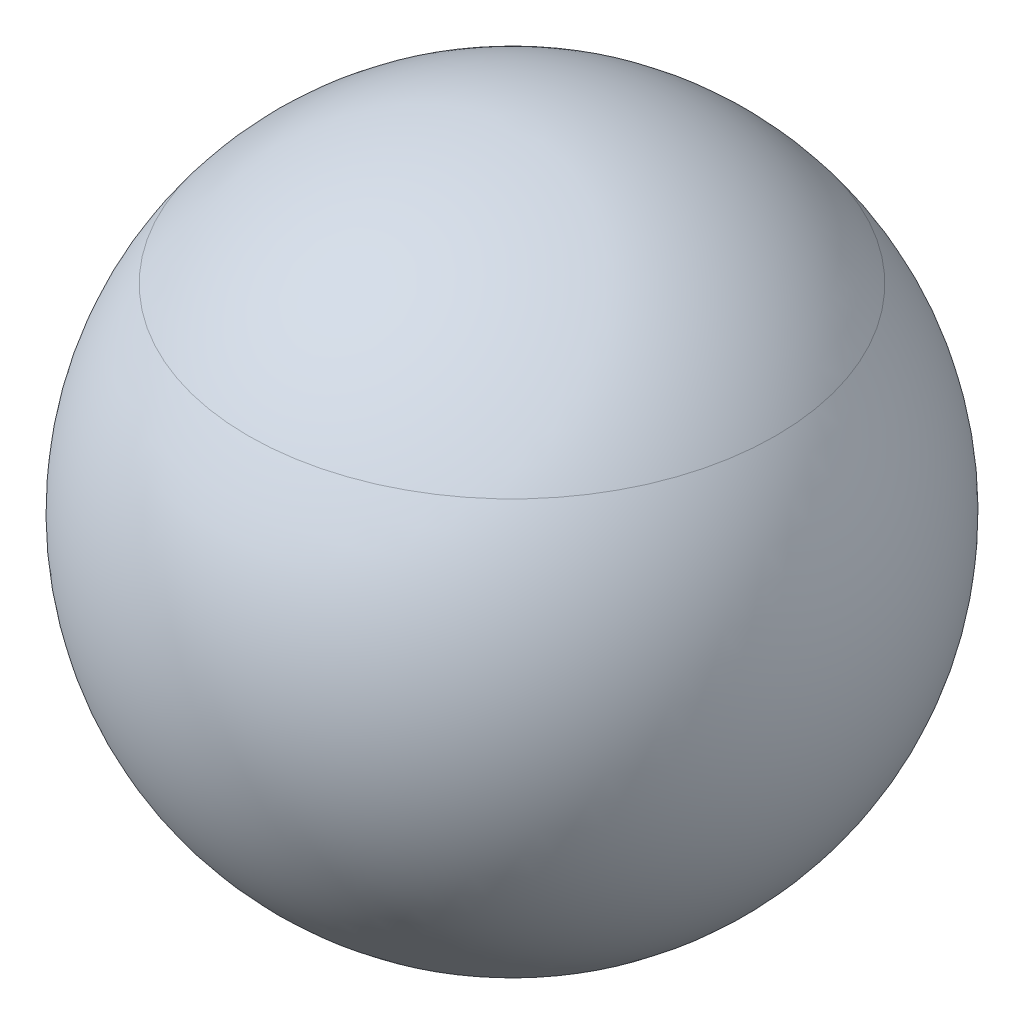
SolidWorks part; units mm, degrees
ref_plane "Front Plane" through (0, 0, 0) normal (0, 0, 1) x (1, 0, 0)
ref_plane "Top Plane" through (0, 0, 0) normal (0, 1, 0) x (1, 0, 0)
ref_plane "Right Plane" through (0, 0, 0) normal (1, 0, 0) x (0, 0, -1)
sketch "Sketch1" plane through (0, 0, 0) normal (0, 0, 1) x (1, 0, 0)
  line L0 (0, 30) -> (0, 0) construction
  line L1 (0, 30) -> (0, 0)
  arc A0 (0, 30) -> (0, 0) centre (0, 15) cw
  dimension "D1" = 30
revolve "Revolve1" add sketch "Sketch1" angle 360 about L0
ref_plane "Plane1" through (0, 24, 0) normal (0, 1, 0) x (1, 0, 0)
split "Split1" trim tools "Plane1" bodies to split 101 resulting bodies 102 103
